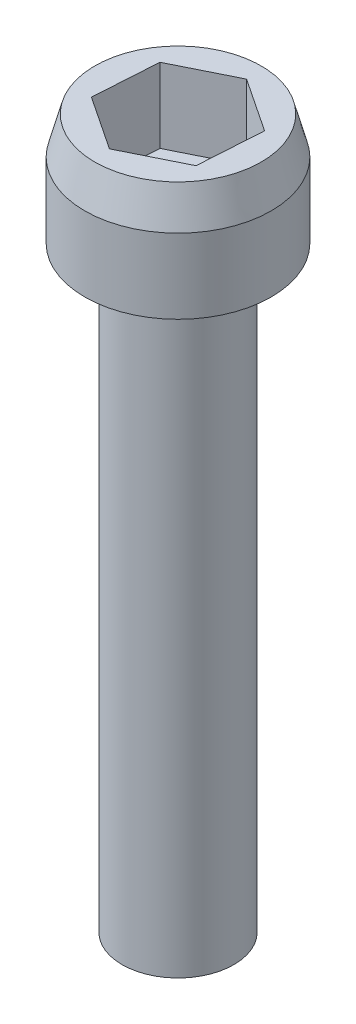
SolidWorks part; units mm, degrees
ref_plane "Přední rovina" through (0, 0, 0) normal (0, 0, 1) x (1, 0, 0)
ref_plane "Horní rovina" through (0, 0, 0) normal (0, 1, 0) x (1, 0, 0)
ref_plane "Pravá rovina" through (0, 0, 0) normal (1, 0, 0) x (0, 0, -1)
sketch "Skica1" plane through (0, 0, 0) normal (0, 1, 0) x (1, 0, 0)
  circle A0 centre (0, 0) radius 1.5
extrude "Přidat vysunutím1" add sketch "Skica1" along normal blind 16
sketch "Skica2" plane through (0, 16, 0) normal (0, 1, 0) x (1, 0, 0)
  circle A0 centre (0, 0) radius 2.5
  dimension "D1" = 5
extrude "Přidat vysunutím2" add sketch "Skica2" along normal blind 3
chamfer "Zkosení1" distance 1 angle 15 1 edges at (0, 19, 2.5)
sketch "Skica3" plane through (0, 19, 0) normal (0, 1, 0) x (1, 0, 0)
  line L1 (-0.1094, -1.7286) -> (1.4423, -0.9591)
  line L2 (1.4423, -0.9591) -> (1.5517, 0.7695)
  line L3 (1.5517, 0.7695) -> (0.1094, 1.7286)
  line L4 (0.1094, 1.7286) -> (-1.4423, 0.9591)
  line L5 (-1.4423, 0.9591) -> (-1.5517, -0.7695)
  line L6 (-1.5517, -0.7695) -> (-0.1094, -1.7286)
  circle A0 centre (0, 0) radius 1.5 construction
extrude "Odebrat vysunutím1" cut sketch "Skica3" against normal blind 2
